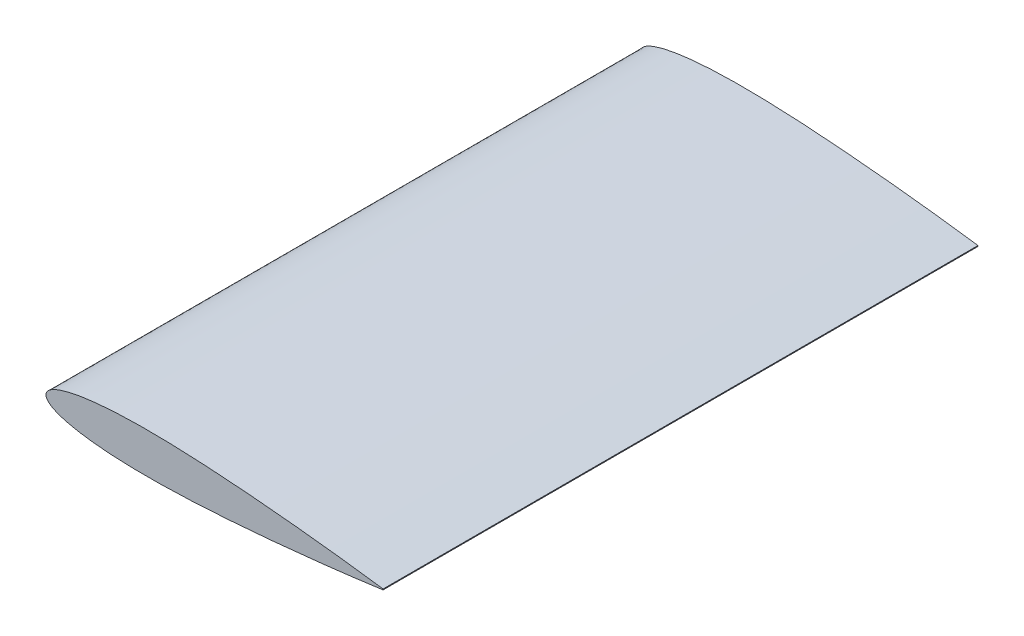
SolidWorks part; units mm, degrees
ref_plane "Front Plane" through (0, 0, 0) normal (0, 0, 1) x (1, 0, 0)
ref_plane "Top Plane" through (0, 0, 0) normal (0, 1, 0) x (1, 0, 0)
ref_plane "Right Plane" through (0, 0, 0) normal (1, 0, 0) x (0, 0, -1)
curve "Curve1"
  spline degree 3 poles (170, 0.2142, 0) (169.9669, 0.2188, 0) (169.8346, 0.2374, 0) (169.5373, 0.279, 0) (169.0426, 0.3481, 0) (168.3516, 0.4442, 0) (167.4659, 0.5667, 0) (166.3876, 0.7147, 0) (165.1192, 0.8874, 0) (163.6637, 1.0836, 0) (162.0245, 1.3022, 0) (160.2054, 1.5419, 0) (158.2106, 1.8012, 0) (156.0449, 2.0787, 0) (153.7132, 2.3729, 0) (151.2211, 2.6822, 0) (148.5743, 3.005, 0) (145.779, 3.3396, 0) (142.8417, 3.6843, 0) (139.7694, 4.0375, 0) (136.5691, 4.3975, 0) (133.2484, 4.7626, 0) (129.815, 5.131, 0) (126.277, 5.501, 0) (122.6425, 5.8707, 0) (118.9201, 6.2384, 0) (115.1185, 6.6021, 0) (111.2466, 6.96, 0) (107.3134, 7.3101, 0) (103.328, 7.6503, 0) (99.2999, 7.9787, 0) (95.2383, 8.2931, 0) (91.1528, 8.5913, 0) (87.053, 8.8711, 0) (82.9484, 9.1303, 0) (78.8485, 9.3668, 0) (74.763, 9.5783, 0) (70.7014, 9.7627, 0) (66.6731, 9.9179, 0) (62.6877, 10.0419, 0) (58.7543, 10.1329, 0) (54.8822, 10.1892, 0) (51.0804, 10.2092, 0) (47.3578, 10.1916, 0) (43.7231, 10.1354, 0) (40.1848, 10.0398, 0) (36.751, 9.9041, 0) (33.4299, 9.7281, 0) (30.2292, 9.5119, 0) (27.1564, 9.2557, 0) (24.2185, 8.9602, 0) (21.4225, 8.6261, 0) (18.7748, 8.2547, 0) (16.2817, 7.8473, 0) (13.9488, 7.4054, 0) (11.7816, 6.9307, 0) (9.785, 6.4252, 0) (7.9635, 5.8907, 0) (6.3212, 5.3291, 0) (4.8614, 4.7425, 0) (3.5873, 4.1325, 0) (2.5009, 3.5004, 0) (1.6038, 2.8472, 0) (0.8975, 2.172, 0) (0.3842, 1.4725, 0) (0.07, 0.7458, 0) (-0.0341, 0, 0) (0.07, -0.7458, 0) (0.3842, -1.4725, 0) (0.8975, -2.172, 0) (1.6038, -2.8472, 0) (2.5009, -3.5004, 0) (3.5873, -4.1325, 0) (4.8614, -4.7425, 0) (6.3212, -5.3291, 0) (7.9635, -5.8907, 0) (9.785, -6.4252, 0) (11.7816, -6.9307, 0) (13.9488, -7.4054, 0) (16.2817, -7.8473, 0) (18.7748, -8.2547, 0) (21.4225, -8.6261, 0) (24.2185, -8.9602, 0) (27.1564, -9.2557, 0) (30.2292, -9.5119, 0) (33.4299, -9.7281, 0) (36.751, -9.9041, 0) (40.1848, -10.0398, 0) (43.7231, -10.1354, 0) (47.3578, -10.1916, 0) (51.0804, -10.2092, 0) (54.8822, -10.1892, 0) (58.7543, -10.1329, 0) (62.6877, -10.0419, 0) (66.6731, -9.9179, 0) (70.7014, -9.7627, 0) (74.763, -9.5783, 0) (78.8485, -9.3668, 0) (82.9484, -9.1303, 0) (87.053, -8.8711, 0) (91.1528, -8.5913, 0) (95.2383, -8.2931, 0) (99.2999, -7.9787, 0) (103.328, -7.6503, 0) (107.3134, -7.3101, 0) (111.2466, -6.96, 0) (115.1185, -6.6021, 0) (118.9201, -6.2384, 0) (122.6425, -5.8707, 0) (126.277, -5.501, 0) (129.815, -5.131, 0) (133.2484, -4.7626, 0) (136.5691, -4.3975, 0) (139.7694, -4.0375, 0) (142.8417, -3.6843, 0) (145.779, -3.3396, 0) (148.5743, -3.005, 0) (151.2211, -2.6822, 0) (153.7132, -2.3729, 0) (156.0449, -2.0787, 0) (158.2106, -1.8012, 0) (160.2054, -1.5419, 0) (162.0245, -1.3022, 0) (163.6637, -1.0836, 0) (165.1192, -0.8874, 0) (166.3876, -0.7147, 0) (167.4659, -0.5667, 0) (168.3516, -0.4442, 0) (169.0426, -0.3481, 0) (169.5373, -0.279, 0) (169.8346, -0.2374, 0) (169.9669, -0.2188, 0) (170, -0.2142, 0) knots 0 0 0 0 0.000289 0.001156 0.002598 0.004612 0.007194 0.010336 0.014031 0.018271 0.023046 0.028343 0.03415 0.040454 0.047239 0.054489 0.062186 0.070314 0.078852 0.08778 0.097077 0.106722 0.116691 0.126961 0.137507 0.148306 0.159331 0.170557 0.181957 0.193504 0.205172 0.216932 0.228758 0.240621 0.252495 0.26435 0.276161 0.287898 0.299536 0.311047 0.322405 0.333584 0.344559 0.355306 0.3658 0.376018 0.385938 0.395538 0.404798 0.413699 0.422222 0.430349 0.438066 0.445357 0.452209 0.458611 0.464554 0.47003 0.475035 0.479569 0.483637 0.48725 0.490432 0.493219 0.495674 0.497891 0.5 0.502109 0.504326 0.506781 0.509568 0.51275 0.516363 0.520431 0.524965 0.52997 0.535446 0.541389 0.547791 0.554643 0.561934 0.569651 0.577778 0.586301 0.595202 0.604462 0.614062 0.623982 0.6342 0.644694 0.655441 0.666416 0.677595 0.688953 0.700464 0.712102 0.723839 0.73565 0.747505 0.759379 0.771242 0.783068 0.794828 0.806496 0.818043 0.829443 0.840669 0.851694 0.862493 0.873039 0.883309 0.893278 0.902923 0.91222 0.921148 0.929686 0.937814 0.945511 0.952761 0.959546 0.96585 0.971657 0.976954 0.981729 0.985969 0.989664 0.992806 0.995388 0.997402 0.998844 0.999711 1 1 1 1
sketch "Sketch1" plane through (0, 0, 0) normal (0, 0, 1) x (1, 0, 0)
  line L0 (170, 0.2142) -> (170, -0.2142)
  spline S0 degree 3 poles (548.5064, 1962.9975) (237.2557, -11.1934) (203.6159, -4.4929) (169.5373, 0.279) (169.0426, 0.3481) (168.3516, 0.4442) (167.4659, 0.5667) (166.3876, 0.7147) (165.1192, 0.8874) (163.6637, 1.0836) (162.0245, 1.3022) (160.2054, 1.5419) (158.2106, 1.8012) (156.0449, 2.0787) (153.7132, 2.3729) (150.2891, 2.7979) (146.6624, 3.2359) (142.8417, 3.6843) (139.7694, 4.0375) (136.5691, 4.3975) (132.0688, 4.8923) (127.423, 5.3844) (121.3751, 5.9996) (116.361, 6.4872) (111.2466, 6.96) (107.3134, 7.3101) (103.328, 7.6503) (99.2999, 7.9787) (95.2383, 8.2931) (91.1528, 8.5913) (87.053, 8.8711) (82.9484, 9.1303) (78.8485, 9.3668) (74.763, 9.5783) (70.7014, 9.7627) (66.6731, 9.9179) (62.6877, 10.0419) (58.7543, 10.1329) (54.8822, 10.1892) (51.0804, 10.2092) (47.3578, 10.1916) (43.7231, 10.1354) (40.1848, 10.0398) (36.751, 9.9041) (33.4299, 9.7281) (30.2292, 9.5119) (27.1564, 9.2557) (24.2185, 8.9602) (21.4225, 8.6261) (18.7748, 8.2547) (16.2817, 7.8473) (13.9488, 7.4054) (11.7816, 6.9307) (9.785, 6.4252) (7.9635, 5.8907) (6.3212, 5.3291) (4.8614, 4.7425) (3.5873, 4.1325) (2.5009, 3.5004) (1.6038, 2.8472) (0.8975, 2.172) (0.3842, 1.4725) (0.07, 0.7458) (-0.0341, 0) (0.07, -0.7458) (0.3842, -1.4725) (0.8975, -2.172) (1.6038, -2.8472) (2.5009, -3.5004) (3.5873, -4.1325) (4.8614, -4.7425) (6.3212, -5.3291) (7.9635, -5.8907) (9.785, -6.4252) (11.7816, -6.9307) (13.9488, -7.4054) (16.2817, -7.8473) (18.7748, -8.2547) (21.4225, -8.6261) (24.2185, -8.9602) (27.1564, -9.2557) (30.2292, -9.5119) (33.4299, -9.7281) (36.751, -9.9041) (40.1848, -10.0398) (43.7231, -10.1354) (47.3578, -10.1916) (51.0804, -10.2092) (54.8822, -10.1892) (58.7543, -10.1329) (62.6877, -10.0419) (66.6731, -9.9179) (70.7014, -9.7627) (74.763, -9.5783) (78.8485, -9.3668) (82.9484, -9.1303) (87.053, -8.8711) (91.1528, -8.5913) (95.2383, -8.2931) (99.2999, -7.9787) (103.328, -7.6503) (107.3134, -7.3101) (111.2466, -6.96) (116.361, -6.4872) (121.3751, -5.9996) (127.423, -5.3844) (132.0688, -4.8923) (136.5691, -4.3975) (139.7694, -4.0375) (143.7747, -3.577) (147.5949, -3.1244) (151.2211, -2.6822) (153.7132, -2.3729) (156.0449, -2.0787) (158.2106, -1.8012) (160.2054, -1.5419) (162.0245, -1.3022) (163.6637, -1.0836) (165.1192, -0.8874) (166.3876, -0.7147) (167.4659, -0.5667) (168.3516, -0.4442) (169.0426, -0.3481) (169.5373, -0.279) (203.6159, 4.4929) (237.2558, 11.1934) (548.5079, -1963.0074) knots -0.295197 -0.295197 -0.295197 -0.295197 0.000289 0.001156 0.002598 0.004612 0.007194 0.010336 0.014031 0.018271 0.023046 0.028343 0.03415 0.040454 0.047239 0.054489 0.070314 0.078852 0.08778 0.097077 0.106722 0.126961 0.137507 0.159331 0.170557 0.181957 0.193504 0.205172 0.216932 0.228758 0.240621 0.252495 0.26435 0.276161 0.287898 0.299536 0.311047 0.322405 0.333584 0.344559 0.355306 0.3658 0.376018 0.385938 0.395538 0.404798 0.413699 0.422222 0.430349 0.438066 0.445357 0.452209 0.458611 0.464554 0.47003 0.475035 0.479569 0.483637 0.48725 0.490432 0.493219 0.495674 0.497891 0.5 0.502109 0.504326 0.506781 0.509568 0.51275 0.516363 0.520431 0.524965 0.52997 0.535446 0.541389 0.547791 0.554643 0.561934 0.569651 0.577778 0.586301 0.595202 0.604462 0.614062 0.623982 0.6342 0.644694 0.655441 0.666416 0.677595 0.688953 0.700464 0.712102 0.723839 0.73565 0.747505 0.759379 0.771242 0.783068 0.794828 0.806496 0.818043 0.829443 0.840669 0.862493 0.873039 0.893278 0.902923 0.91222 0.921148 0.937814 0.945511 0.952761 0.959546 0.96585 0.971657 0.976954 0.981729 0.985969 0.989664 0.992806 0.995388 0.997402 0.998844 0.999711 1.295198 1.295198 1.295198 1.295198 only from (170, 0.2142) to (170, -0.2142) construction
  spline S1 degree 3 poles (170, 0.2142) (169.9669, 0.2188) (169.8346, 0.2374) (169.5373, 0.279) (169.0426, 0.3481) (168.3516, 0.4442) (167.4659, 0.5667) (166.3876, 0.7147) (165.1192, 0.8874) (163.6637, 1.0836) (162.0245, 1.3022) (160.2054, 1.5419) (158.2106, 1.8012) (156.0449, 2.0787) (153.7132, 2.3729) (150.2891, 2.7979) (146.6624, 3.2359) (142.8417, 3.6843) (139.7694, 4.0375) (136.5691, 4.3975) (132.0688, 4.8923) (127.423, 5.3844) (121.3751, 5.9996) (116.361, 6.4872) (111.2466, 6.96) (107.3134, 7.3101) (103.328, 7.6503) (99.2999, 7.9787) (95.2383, 8.2931) (91.1528, 8.5913) (87.053, 8.8711) (82.9484, 9.1303) (78.8485, 9.3668) (74.763, 9.5783) (70.7014, 9.7627) (66.6731, 9.9179) (62.6877, 10.0419) (58.7543, 10.1329) (54.8822, 10.1892) (51.0804, 10.2092) (47.3578, 10.1916) (43.7231, 10.1354) (40.1848, 10.0398) (36.751, 9.9041) (33.4299, 9.7281) (30.2292, 9.5119) (27.1564, 9.2557) (24.2185, 8.9602) (21.4225, 8.6261) (18.7748, 8.2547) (16.2817, 7.8473) (13.9488, 7.4054) (11.7816, 6.9307) (9.785, 6.4252) (7.9635, 5.8907) (6.3212, 5.3291) (4.8614, 4.7425) (3.5873, 4.1325) (2.5009, 3.5004) (1.6038, 2.8472) (0.8975, 2.172) (0.3842, 1.4725) (0.07, 0.7458) (-0.0341, 0) (0.07, -0.7458) (0.3842, -1.4725) (0.8975, -2.172) (1.6038, -2.8472) (2.5009, -3.5004) (3.5873, -4.1325) (4.8614, -4.7425) (6.3212, -5.3291) (7.9635, -5.8907) (9.785, -6.4252) (11.7816, -6.9307) (13.9488, -7.4054) (16.2817, -7.8473) (18.7748, -8.2547) (21.4225, -8.6261) (24.2185, -8.9602) (27.1564, -9.2557) (30.2292, -9.5119) (33.4299, -9.7281) (36.751, -9.9041) (40.1848, -10.0398) (43.7231, -10.1354) (47.3578, -10.1916) (51.0804, -10.2092) (54.8822, -10.1892) (58.7543, -10.1329) (62.6877, -10.0419) (66.6731, -9.9179) (70.7014, -9.7627) (74.763, -9.5783) (78.8485, -9.3668) (82.9484, -9.1303) (87.053, -8.8711) (91.1528, -8.5913) (95.2383, -8.2931) (99.2999, -7.9787) (103.328, -7.6503) (107.3134, -7.3101) (111.2466, -6.96) (116.361, -6.4872) (121.3751, -5.9996) (127.423, -5.3844) (132.0688, -4.8923) (136.5691, -4.3975) (139.7694, -4.0375) (143.7747, -3.577) (147.5949, -3.1244) (151.2211, -2.6822) (153.7132, -2.3729) (156.0449, -2.0787) (158.2106, -1.8012) (160.2054, -1.5419) (162.0245, -1.3022) (163.6637, -1.0836) (165.1192, -0.8874) (166.3876, -0.7147) (167.4659, -0.5667) (168.3516, -0.4442) (169.0426, -0.3481) (169.5373, -0.279) (169.8346, -0.2374) (169.9669, -0.2188) (170, -0.2142) knots 0 0 0 0 0.000289 0.001156 0.002598 0.004612 0.007194 0.010336 0.014031 0.018271 0.023046 0.028343 0.03415 0.040454 0.047239 0.054489 0.070314 0.078852 0.08778 0.097077 0.106722 0.126961 0.137507 0.159331 0.170557 0.181957 0.193504 0.205172 0.216932 0.228758 0.240621 0.252495 0.26435 0.276161 0.287898 0.299536 0.311047 0.322405 0.333584 0.344559 0.355306 0.3658 0.376018 0.385938 0.395538 0.404798 0.413699 0.422222 0.430349 0.438066 0.445357 0.452209 0.458611 0.464554 0.47003 0.475035 0.479569 0.483637 0.48725 0.490432 0.493219 0.495674 0.497891 0.5 0.502109 0.504326 0.506781 0.509568 0.51275 0.516363 0.520431 0.524965 0.52997 0.535446 0.541389 0.547791 0.554643 0.561934 0.569651 0.577778 0.586301 0.595202 0.604462 0.614062 0.623982 0.6342 0.644694 0.655441 0.666416 0.677595 0.688953 0.700464 0.712102 0.723839 0.73565 0.747505 0.759379 0.771242 0.783068 0.794828 0.806496 0.818043 0.829443 0.840669 0.862493 0.873039 0.893278 0.902923 0.91222 0.921148 0.937814 0.945511 0.952761 0.959546 0.96585 0.971657 0.976954 0.981729 0.985969 0.989664 0.992806 0.995388 0.997402 0.998844 0.999711 1 1 1 1
extrude "Boss-Extrude1" add sketch "Sketch1" along normal blind 300
